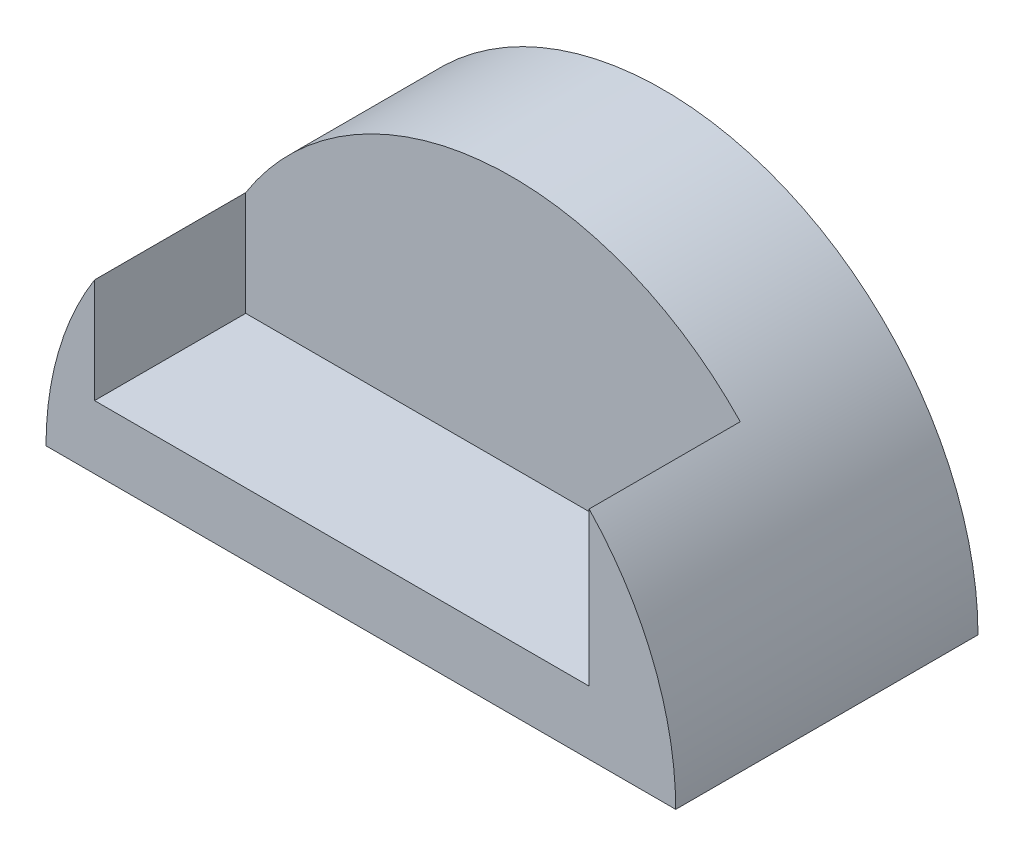
SolidWorks part; units mm, degrees
ref_plane "Front Plane" through (0, 0, 0) normal (0, 0, 1) x (1, 0, 0)
ref_plane "Top Plane" through (0, 0, 0) normal (0, 1, 0) x (1, 0, 0)
ref_plane "Right Plane" through (0, 0, 0) normal (1, 0, 0) x (0, 0, -1)
sketch "Sketch1" plane through (0, 0, 0) normal (0, 0, 1) x (1, 0, 0)
  line L0 (-15.875, 0) -> (15.875, 0)
  arc A0 (15.875, 0) -> (-15.875, 0) centre (0, 0) ccw
  dimension "D1" = 31.75
extrude "Boss-Extrude1" add sketch "Sketch1" along normal mid plane 15.24
sketch "Sketch2" plane through (0, 0, 0) normal (0, 0, 1) x (1, 0, 0)
  line L0 (-13.4267, 3.1987) -> (11.5086, 3.1987)
  line L1 (-15.875, 0) -> (15.875, 0)
  line L2 (-15.875, 0) -> (15.875, 0)
  line L3 (-13.4267, 3.1987) -> (-13.4267, 17.3587)
  line L4 (11.5086, 3.1987) -> (11.5086, 17.3587)
  line L5 (11.5086, 17.3587) -> (-13.4267, 17.3587)
  arc A1 (15.875, 0) -> (-15.875, 0) centre (0, 0) ccw
  arc A2 (15.875, 0) -> (-15.875, 0) centre (0, 0) ccw
  point P7 (-13.4267, 14.8201)
  dimension "D1" = 0
extrude "Cut-Extrude1" cut sketch "Sketch2" along normal through all contours L4 A2 L3 L0
